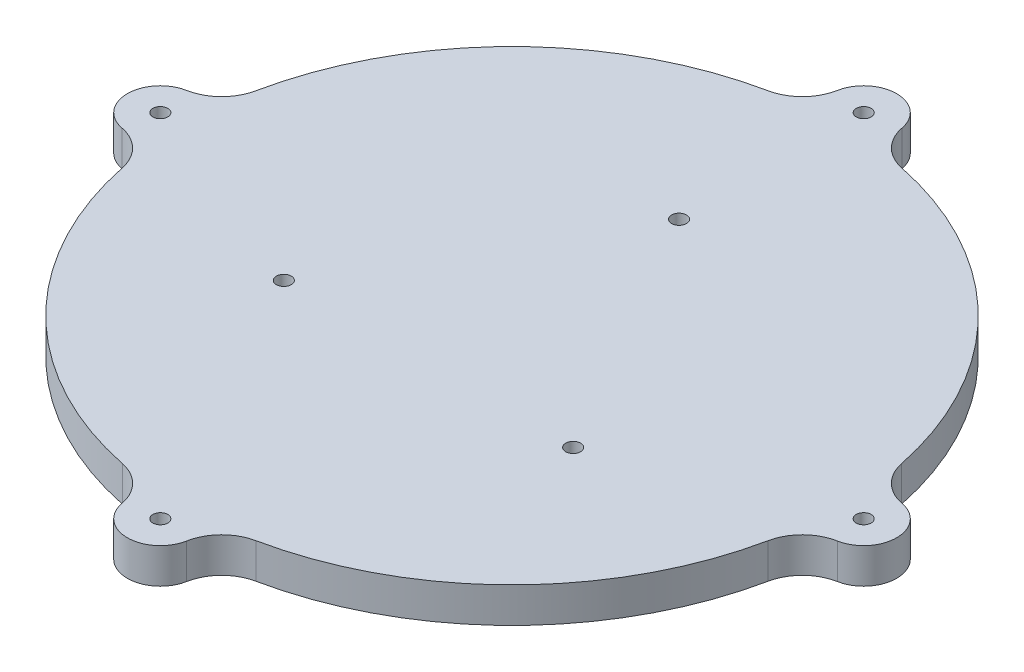
SolidWorks part; units mm, degrees
ref_plane "Front Plane" through (0, 0, 0) normal (0, 0, 1) x (1, 0, 0)
ref_plane "Top Plane" through (0, 0, 0) normal (0, 1, 0) x (1, 0, 0)
ref_plane "Right Plane" through (0, 0, 0) normal (1, 0, 0) x (0, 0, -1)
sketch "Sketch1" plane through (0, 0, 0) normal (0, 1, 0) x (1, 0, 0)
  line L0 (0, 0) -> (0, 80) construction
  circle A0 centre (0, 0) radius 75
  circle A1 centre (0, 80) radius 1.7
  circle A2 centre (0, 80) radius 7.5
  circle A3 centre (80, 0) radius 7.5
  circle A4 centre (80, 0) radius 1.7
  circle A5 centre (0, -80) radius 7.5
  circle A6 centre (0, -80) radius 1.7
  circle A7 centre (-80, 0) radius 7.5
  circle A8 centre (-80, 0) radius 1.7
  point P18 (0, 0)
  dimension "D1" = 150
  dimension "D3" = 3.4
  dimension "D4" = 15
  dimension "D2" = 80
  dimension "D5" = 4
extrude "Boss-Extrude1" add sketch "Sketch1" along normal blind 8
fillet "Fillet1" radius 10 8 edges at (5.4091, 4, 74.8047) (-5.4091, 4, 74.8047) (74.8047, 4, -5.4091) (74.8047, 4, 5.4091) (-5.4091, 4, -74.8047) (5.4091, 4, -74.8047) (-74.8047, 4, 5.4091) (-74.8047, 4, -5.4091)
sketch "Sketch2" plane through (0, 8, 0) normal (0, 1, 0) x (1, 0, 0)
  line L0 (0, 0) -> (0, 38) construction
  line L1 (0, 0) -> (32.909, -19) construction
  line L2 (0, 0) -> (-32.909, -19) construction
  circle A0 centre (0, 38) radius 1.7
  circle A1 centre (32.909, -19) radius 1.7
  circle A2 centre (-32.909, -19) radius 1.7
  dimension "D7" = 3.4
  dimension "D8" = 3.4
  dimension "D9" = 3.4
  dimension "D1" = 38
  dimension "D2" = 38
  dimension "D3" = 38
  dimension "D4" = 120
  dimension "D5" = 120
  dimension "D6" = 120
extrude "Cut-Extrude1" cut sketch "Sketch2" against normal blind 39
